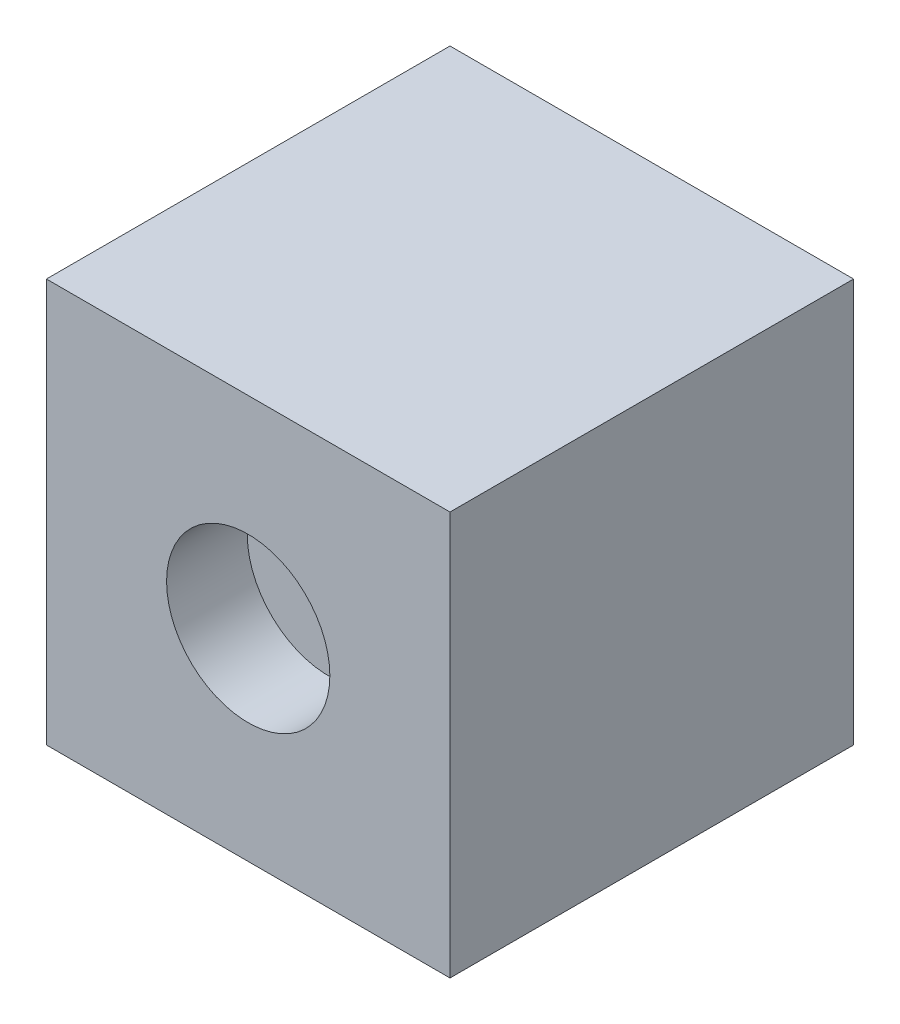
SolidWorks part; units mm, degrees
ref_plane "Front Plane" through (0, 0, 0) normal (0, 0, 1) x (1, 0, 0)
ref_plane "Top Plane" through (0, 0, 0) normal (0, 1, 0) x (1, 0, 0)
ref_plane "Right Plane" through (0, 0, 0) normal (1, 0, 0) x (0, 0, -1)
sketch "Sketch1" plane through (0, 0, 0) normal (0, 0, 1) x (1, 0, 0)
  line L1 (-25, 25) -> (25, 25)
  line L2 (-25, 25) -> (-25, -25)
  line L3 (-25, -25) -> (25, -25)
  line L4 (25, 25) -> (25, -25)
  line L5 (-25, 25) -> (25, -25) construction
  line L6 (-25, -25) -> (25, 25) construction
  point P0 (0, 0)
  dimension "D1" = 50
  dimension "D2" = 50
extrude "Boss-Extrude1" add sketch "Sketch1" along normal blind 50
sketch "Sketch2" plane through (0, 0, 50) normal (0, 0, 1) x (1, 0, 0)
  circle A0 centre (0, 0) radius 10.114
extrude "Cut-Extrude1" cut sketch "Sketch2" against normal blind 10
